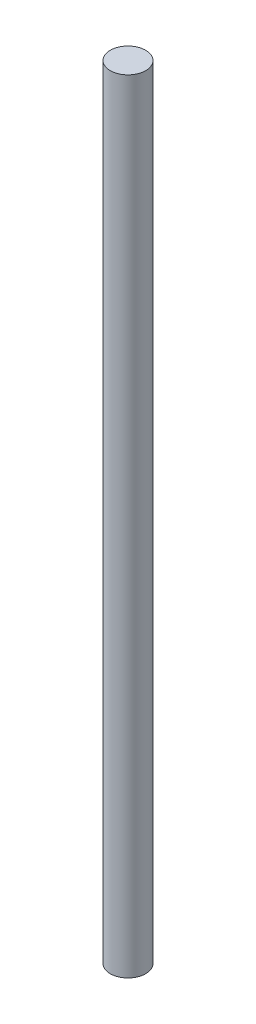
SolidWorks part; units mm, degrees
material "6061-T6 (SS)"
ref_plane "Front Plane" through (0, 0, 0) normal (1, 0, 0) x (0, 1, 0)
ref_plane "Top Plane" through (0, 0, 0) normal (0, 0, 1) x (0, 1, 0)
ref_plane "Right Plane" through (0, 0, 0) normal (0, 1, 0) x (-1, 0, 0)
other "Center of Mass"
sketch "Sketch1" plane through (0, 0, 0) normal (0, 1, 0) x (-1, 0, 0)
  circle A0 centre (0, 0) radius 1.5875
  dimension "D1" = 3.175
extrude "Boss-Extrude1" add sketch "Sketch1" along normal blind 70.1869 contours A0
equation "\"diameter\"= 0.125in"
equation "\"F_axial\"= 400'In units: lbf"
equation "\"E\"= 10007600'In units: psi"
equation "\"del_axial_max\"= 0.009in"
equation "\"L_bar\"= \"del_axial_max\" * ( pi / 4 ) * ( ( \"diameter\" / 1in ) ^ 2 ) * \"E\" / \"F_axial\"'In units: in"
equation "\"D1@Boss-Extrude1\"=\"L_bar\""
